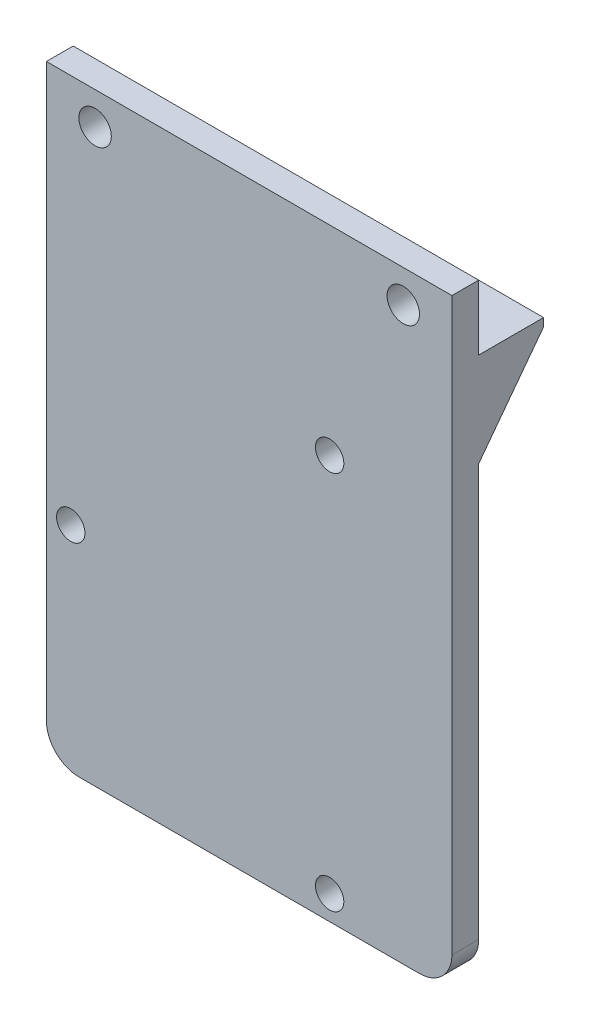
SolidWorks part; units mm, degrees
ref_plane "正面" through (0, 0, 0) normal (0, 0, 1) x (1, 0, 0)
ref_plane "平面" through (0, 0, 0) normal (0, 1, 0) x (1, 0, 0)
ref_plane "右側面" through (0, 0, 0) normal (1, 0, 0) x (0, 0, -1)
sketch "ｽｹｯﾁ1" plane through (0, 0, 0) normal (0, 0, 1) x (1, 0, 0)
  line L0 (0, 0) -> (0, -46.8) construction
  line L1 (-31.92, -23.4) -> (16.6702, -23.4) construction
  line L2 (15.08, 24.6) -> (-34.92, 24.6)
  line L3 (15.08, 24.6) -> (15.08, -49.8)
  line L4 (15.08, -49.8) -> (-34.92, -49.8)
  line L5 (-34.92, 24.6) -> (-34.92, -49.8)
  line L6 (-9.92, 21.6152) -> (-9.92, -63.515) construction
  circle A0 centre (0, 0) radius 1.75
  circle A1 centre (0, -46.8) radius 1.75
  circle A2 centre (-31.92, -23.4) radius 1.75
  circle A3 centre (9.08, 20.6) radius 2
  circle A4 centre (-28.92, 20.6) radius 2
  dimension "D2" = 3.5
  dimension "D13" = 4
  dimension "D14" = 4
  dimension "D1" = 31.92
  dimension "D3" = 23.4
  dimension "D4" = 23.4
  dimension "D5" = 50
  dimension "D6" = 3
  dimension "D7" = 3
  dimension "D8" = 48
  dimension "D9" = 19
  dimension "D10" = 19
  dimension "D11" = 4
  dimension "D12" = 4
extrude "ﾎﾞｽ - 押し出し2" add sketch "ｽｹｯﾁ1" along normal blind 3.3 contours L2 L5 L4 L3 A2 A1 A0
fillet "ﾌｨﾚｯﾄ1" radius 4 2 edges at (15.08, -49.8, 1.65) (-34.92, -49.8, 1.65)
sketch "ｽｹｯﾁ3" plane through (15.08, 0, 0) normal (1, 0, 0) x (0, 0, -1)
  line L0 (0, 16.6) -> (8, 16.6)
  line L1 (0, 24.6) -> (0, -45.8) construction
  line L3 (0, 5) -> (0, 16.6)
  line L4 (-3.3, 24.6) -> (0, 24.6) construction
  line L5 (8, 16.6) -> (8, 15.6)
  line L6 (8, 15.6) -> (0, 5)
  dimension "D1" = 8
  dimension "D2" = 8
  dimension "D3" = 5
  dimension "D4" = 1
extrude "ﾎﾞｽ - 押し出し3" add sketch "ｽｹｯﾁ3" against normal up to surface (50 mm away) up to face at (-34.92, -10.6, 1.65)
